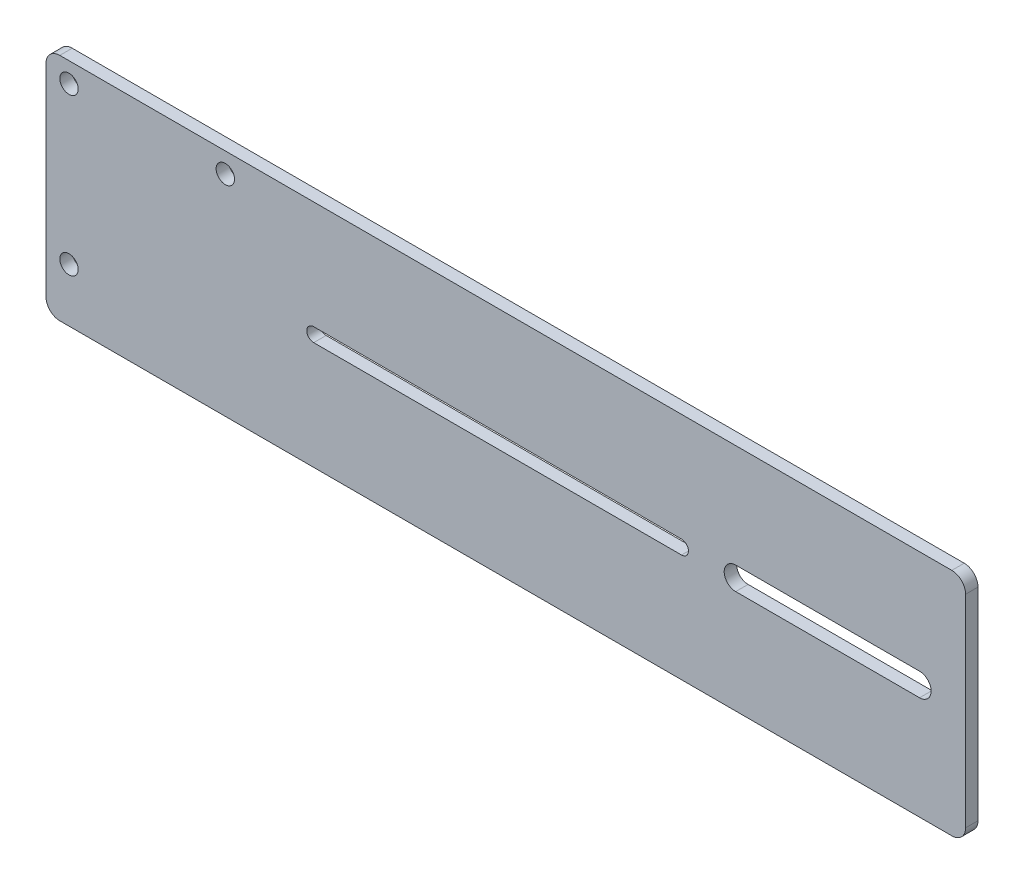
SolidWorks part; units mm, degrees
ref_plane "前视基准面" through (0, 0, 0) normal (0, 0, 1) x (1, 0, 0)
ref_plane "上视基准面" through (0, 0, 0) normal (0, 1, 0) x (1, 0, 0)
ref_plane "右视基准面" through (0, 0, 0) normal (1, 0, 0) x (0, 0, -1)
sketch "草图1" plane through (0, 0, 0) normal (0, 0, 1) x (1, 0, 0)
  line L0 (0, 22) -> (0, -22)
  line L1 (3, 25) -> (197, 25)
  line L3 (3, -25) -> (197, -25)
  line L4 (200, 22) -> (200, -22)
  line L9 (150, 2.5) -> (190, 2.5)
  line L10 (190, -2.5) -> (150, -2.5)
  line L11 (58.2194, 1.5) -> (138.2194, 1.5)
  line L15 (0, 0) -> (150, 0) construction
  line L16 (138.2194, -1.5) -> (58.2194, -1.5)
  arc A0 (200, -22) -> (197, -25) centre (197, -22) cw
  arc A1 (200, 22) -> (197, 25) centre (197, 22) ccw
  arc A2 (0, -22) -> (3, -25) centre (3, -22) ccw
  arc A3 (0, 22) -> (3, 25) centre (3, 22) cw
  circle A8 centre (5, 20.65) radius 2
  circle A9 centre (39, 20.65) radius 2
  circle A10 centre (5, -13.35) radius 2
  arc A11 (150, 2.5) -> (150, -2.5) centre (150, 0) ccw
  arc A12 (190, -2.5) -> (190, 2.5) centre (190, 0) ccw
  arc A17 (58.2194, 1.5) -> (58.2194, -1.5) centre (58.2194, 0) ccw
  arc A18 (138.2194, -1.5) -> (138.2194, 1.5) centre (138.2194, 0) ccw
  point P13 (68.627, -14.3433)
  dimension "D1" = 3
  dimension "D2" = 5
  dimension "D4" = 10
  dimension "D7" = 80
  dimension "D5" = 40
  dimension "D6" = 200
extrude "凸台-拉伸1" add sketch "草图1" along normal blind 2.7 contours A3 L0 A2 L3 A0 L4 A1 L1 A12 L10 A11 L9 A10 A9 A8
